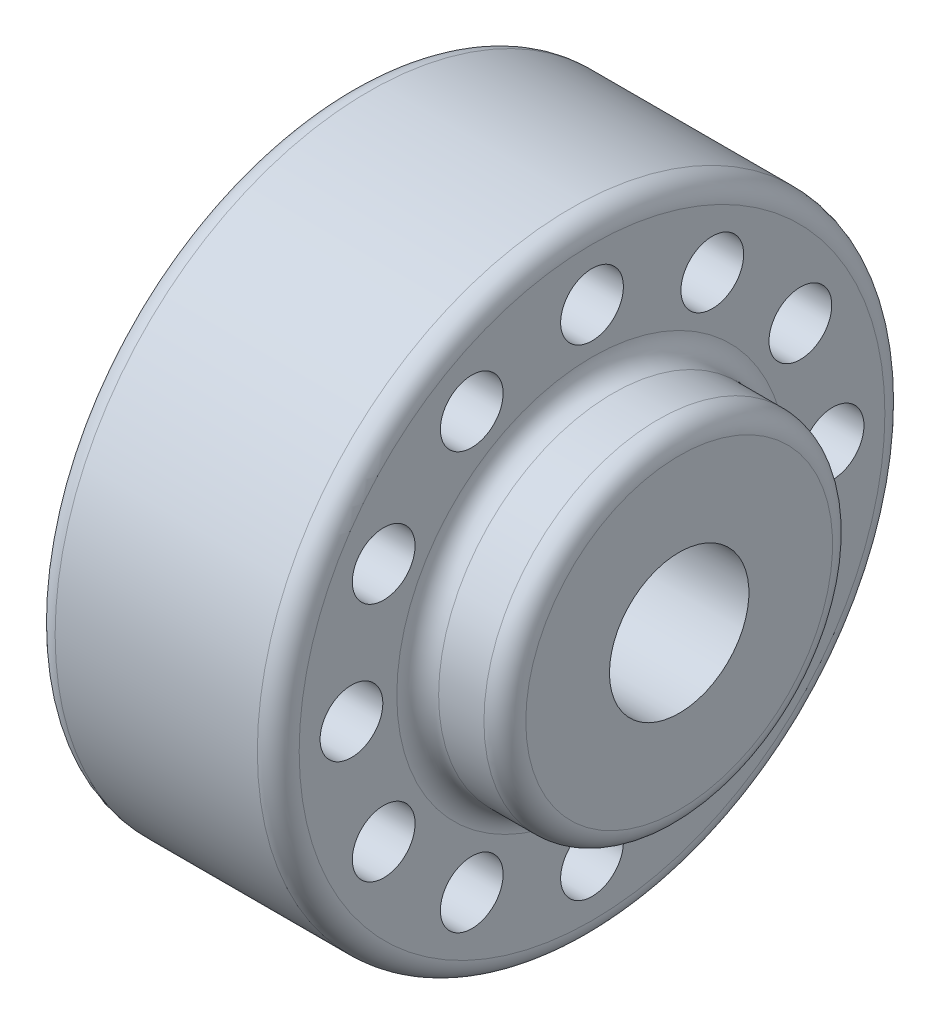
SolidWorks part; units mm, degrees
ref_plane "Front Plane" through (0, 0, 0) normal (0, 0, 1) x (1, 0, 0)
ref_plane "Top Plane" through (0, 0, 0) normal (0, 1, 0) x (1, 0, 0)
ref_plane "Right Plane" through (0, 0, 0) normal (1, 0, 0) x (0, 0, -1)
sketch "Sketch1" plane through (0, 0, 0) normal (0, 0, 1) x (1, 0, 0)
  line L0 (0, 0) -> (0, 45) construction
  line L1 (14.5, 45) -> (-14.5, 45)
  line L2 (-17.5, 42) -> (-17.5, 28)
  line L3 (-20.5, 25) -> (-27, 25)
  line L4 (-30, 22) -> (-30, 10)
  line L6 (30, 22) -> (30, 10)
  line L7 (20.5, 25) -> (27, 25)
  line L8 (17.5, 42) -> (17.5, 28)
  line L9 (45.7186, 0) -> (75.5389, 0) construction
  line L10 (-30, 10) -> (30, 10)
  arc A0 (30, 22) -> (27, 25) centre (27, 22) ccw
  arc A1 (20.5, 25) -> (17.5, 28) centre (20.5, 28) cw
  arc A2 (17.5, 42) -> (14.5, 45) centre (14.5, 42) ccw
  arc A3 (-17.5, 28) -> (-20.5, 25) centre (-20.5, 28) cw
  arc A4 (-14.5, 45) -> (-17.5, 42) centre (-14.5, 42) ccw
  arc A5 (-27, 25) -> (-30, 22) centre (-27, 22) ccw
  point P15 (30, 25)
  point P18 (17.5, 25)
  point P21 (17.5, 45)
  point P24 (-17.5, 25)
  point P27 (-17.5, 45)
  point P30 (-30, 25)
  dimension "D6" = 3
  dimension "D1" = 60
  dimension "D2" = 35
  dimension "D3" = 90
  dimension "D4" = 10
  dimension "D5" = 50
revolve "Revolve1" add sketch "Sketch1" angle 360 about L9
sketch "Sketch2" plane through (17.5, 0, 0) normal (1, 0, 0) x (0, 0, -1)
  circle A0 centre (0, 34.5) radius 4.5
  point P2 (0, 34.5)
  dimension "D2" = 9
  dimension "D1" = 34.5
extrude "Cut-Extrude1" cut sketch "Sketch2" against normal through all
pattern_circular "CirPattern1" count 12 over 360 about axis through (0, 0, 0) along (1, 0, 0) of "Cut-Extrude1"
